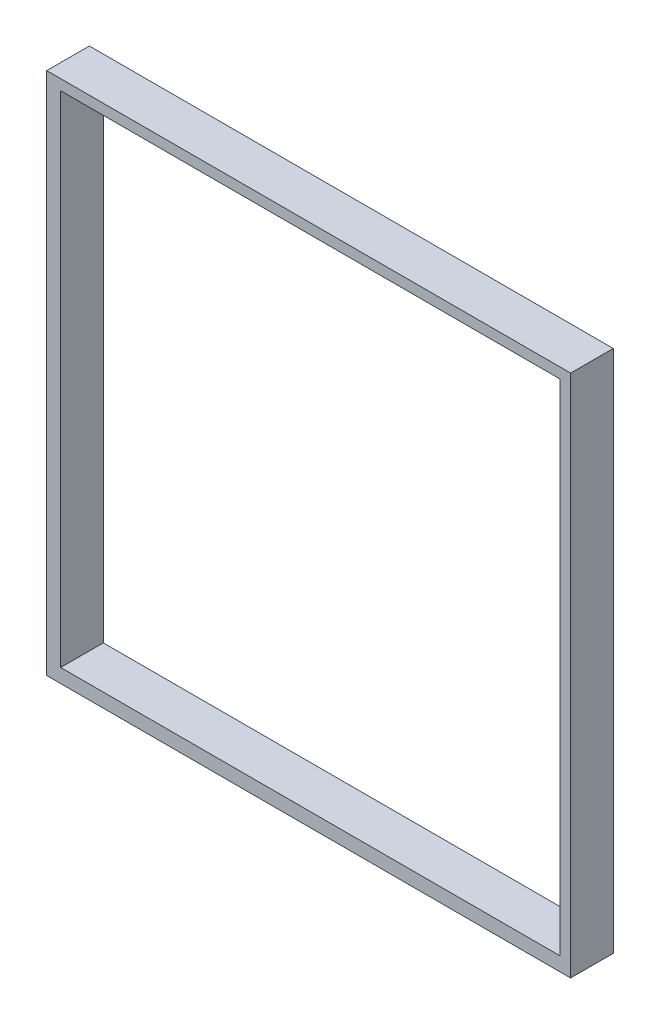
SolidWorks part; units mm, degrees
ref_plane "Piano frontale" through (0, 0, 0) normal (0, 0, 1) x (1, 0, 0)
ref_plane "Piano superiore" through (0, 0, 0) normal (0, 1, 0) x (1, 0, 0)
ref_plane "Piano destro" through (0, 0, 0) normal (1, 0, 0) x (0, 0, -1)
sketch "Schizzo1" plane through (0, 0, 0) normal (0, 0, 1) x (1, 0, 0)
  line L1 (0, 0) -> (43, 0)
  line L2 (0, 0) -> (0, 43)
  line L3 (0, 43) -> (43, 43)
  line L4 (43, 0) -> (43, 43)
  dimension "D1" = 43
  dimension "D2" = 43
extrude "Estrusione-Estrusione1" add sketch "Schizzo1" along normal blind 3.5
sketch "Schizzo8" plane through (0, 0, 0) normal (0, 0, -1) x (-1, 0, 0)
  line L1 (-42.1428, 42.1428) -> (-1.1428, 42.1428)
  line L2 (-42.1428, 42.1428) -> (-42.1428, 1.1428)
  line L3 (-42.1428, 1.1428) -> (-1.1428, 1.1428)
  line L4 (-1.1428, 42.1428) -> (-1.1428, 1.1428)
  dimension "D1" = 41
  dimension "D2" = 41
extrude "Taglio-Estrusione1" cut sketch "Schizzo8" against normal blind 15.5
